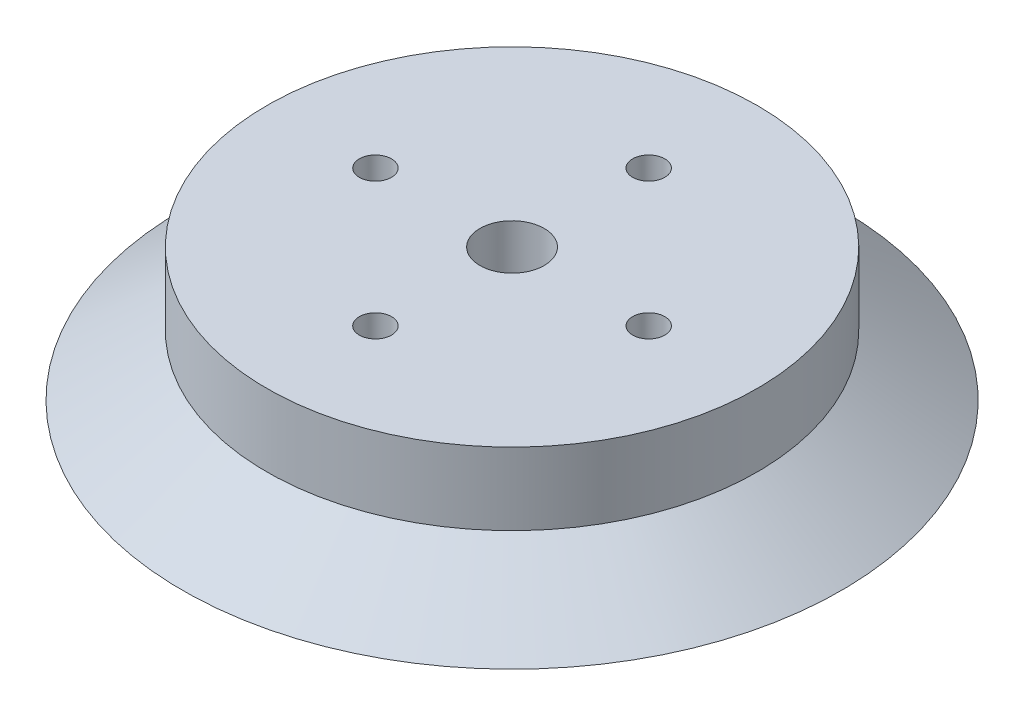
SolidWorks part; units mm, degrees
material "橡胶"
ref_plane "前视基准面" through (0, 0, 0) normal (0, 0, 1) x (1, 0, 0)
ref_plane "上视基准面" through (0, 0, 0) normal (0, 1, 0) x (1, 0, 0)
ref_plane "右视基准面" through (0, 0, 0) normal (1, 0, 0) x (0, 0, -1)
sketch "草图1" plane through (0, 0, 0) normal (0, 0, 1) x (1, 0, 0)
  line L0 (0, 0) -> (0, 16.5) construction
  line L1 (0, 16.5) -> (-30.5, 16.5)
  line L2 (-30.5, 16.5) -> (-30.5, 7.5)
  line L3 (-30.5, 7.5) -> (-41, 0)
  line L4 (-41, 0) -> (-37.5591, 0)
  line L5 (-37.5591, 0) -> (-27.0591, 7.5)
  line L6 (-27.0591, 7.5) -> (0, 7.5)
  line L7 (0, 16.5) -> (0, 7.5)
  point P11 (-53.3463, 46.3059)
  dimension "D1" = 30.5
  dimension "D2" = 9
  dimension "D3" = 9
  dimension "D4" = 16.5
  dimension "D5" = 41
  dimension "D6" = 2
revolve "旋转1" add sketch "草图1" angle 360 about L0
sketch "草图2" plane through (0, 7.5, 0) normal (0, -1, 0) x (1, 0, 0)
  circle A0 centre (0, 0) radius 4
  circle A1 centre (0, 0) radius 17 construction
  circle A2 centre (0, 17) radius 2
  circle A3 centre (17, 0) radius 2
  circle A4 centre (0, -17) radius 2
  circle A5 centre (-17, 0) radius 2
  point P15 (0, 0)
  dimension "D1" = 8
  dimension "D2" = 34
  dimension "D3" = 4
  dimension "D4" = 4
extrude "切除-拉伸1" cut sketch "草图2" against normal blind 10
